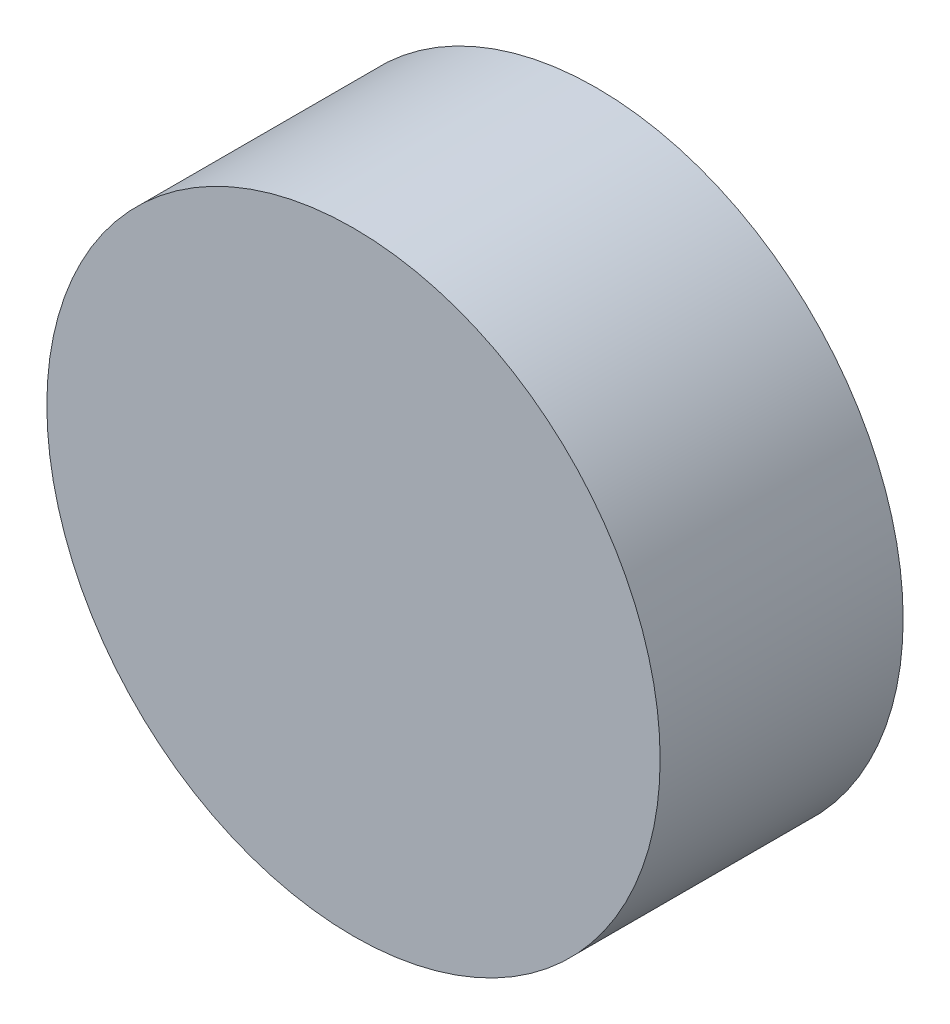
SolidWorks part; units mm, degrees
ref_plane "Front Plane" through (0, 0, 0) normal (0, 0, 1) x (1, 0, 0)
ref_plane "Top Plane" through (0, 0, 0) normal (0, 1, 0) x (1, 0, 0)
ref_plane "Right Plane" through (0, 0, 0) normal (1, 0, 0) x (0, 0, -1)
sketch "Sketch1" plane through (0, 0, 0) normal (0, 0, 1) x (1, 0, 0)
  circle A0 centre (0, 0) radius 53
extrude "Boss-Extrude1" add sketch "Sketch1" along normal blind 42 contours A0
